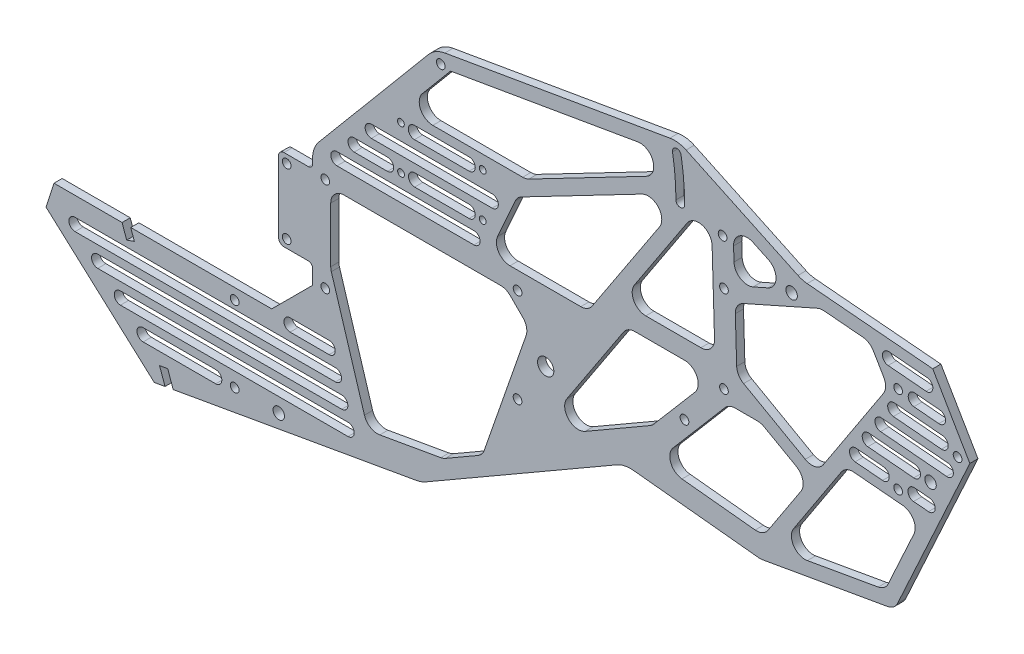
SolidWorks part; units mm, degrees
ref_plane "Front Plane" through (0, 0, 0) normal (0, 0, 1) x (1, 0, 0)
ref_plane "Top Plane" through (0, 0, 0) normal (0, 1, 0) x (1, 0, 0)
ref_plane "Right Plane" through (0, 0, 0) normal (1, 0, 0) x (0, 0, -1)
sketch "Sketch1" plane through (0, 0, 0) normal (0, 0, 1) x (1, 0, 0)
  line L0 (-2, -20.1357) -> (-28.6473, -20.1357) construction
  line L1 (-28.6473, -15.5958) -> (-2, -15.5958) construction
  line L2 (46.6267, -12.6057) -> (-36.9862, -12.6057) construction
  line L3 (-36.9862, -8.0658) -> (46.6267, -8.0658) construction
  line L4 (44.3092, -5.0757) -> (-45.3251, -5.0757) construction
  line L5 (-45.3251, -0.5358) -> (44.3092, -0.5358) construction
  line L6 (41.9917, 2.4543) -> (-53.664, 2.4543) construction
  line L7 (-53.664, 6.9942) -> (41.9917, 6.9942) construction
  line L8 (39.6742, 9.9843) -> (25.3518, 9.9843) construction
  line L9 (25.3518, 14.5242) -> (39.6742, 14.5242) construction
  line L10 (-2, -20.1357) -> (-28.6473, -20.1357)
  line L11 (-28.6473, -15.5958) -> (-2, -15.5958)
  line L12 (46.6267, -12.6057) -> (-36.9862, -12.6057)
  line L13 (-36.9862, -8.0658) -> (46.6267, -8.0658)
  line L14 (44.3092, -5.0757) -> (-45.3251, -5.0757)
  line L15 (-45.3251, -0.5358) -> (44.3092, -0.5358)
  line L16 (41.9917, 2.4543) -> (-53.664, 2.4543)
  line L17 (-53.664, 6.9942) -> (41.9917, 6.9942)
  line L18 (39.6742, 9.9843) -> (25.3518, 9.9843)
  line L19 (25.3518, 14.5242) -> (39.6742, 14.5242)
  line L20 (80.7464, -2.2866) -> (58.3209, -6.2408) construction
  line L21 (106.2441, 62.0298) -> (110.8759, 57.3979) construction
  line L22 (45.2764, 63.4942) -> (102.7085, 63.4942) construction
  line L23 (40.2764, 38.2462) -> (40.2764, 58.4942) construction
  line L24 (52.6739, -2.7875) -> (40.4976, 36.7755) construction
  line L25 (112.0626, 52.2191) -> (96.66, 7.9568) construction
  line L26 (33.6064, 69.3545) -> (33.6064, 67.4942)
  line L27 (76.2479, 123.8124) -> (35.946, 75.7824)
  line L28 (164.9022, 141.4902) -> (82.21, 127.2392)
  line L29 (211.9524, 121.3273) -> (170.8618, 140.6821)
  line L30 (261.4848, 116.375) -> (215.3421, 120.412)
  line L31 (275.1174, 93.0694) -> (261.4848, 116.375)
  line L32 (266.371, 74.0309) -> (275.1174, 93.0694)
  line L33 (151.4467, 29.0597) -> (212.4327, 22.7334)
  line L34 (75.0971, -12.8246) -> (145.4149, 27.7734)
  line L35 (-17.6047, -29.7828) -> (71.8336, -14.0124)
  line L36 (-19.6192, -24.1311) -> (-17.6047, -29.7828)
  line L37 (-22.6157, -24.6595) -> (-19.6192, -24.1311)
  line L38 (-20.6012, -30.3112) -> (-22.6157, -24.6595)
  line L39 (-24.5404, -31.0058) -> (-20.6012, -30.3112)
  line L40 (-64.3382, 4.9315) -> (-24.5404, -31.0058)
  line L41 (-61.3936, 13.9942) -> (-64.3382, 4.9315)
  line L42 (-36.3936, 13.9942) -> (-61.3936, 13.9942)
  line L43 (-34.6915, 9.2192) -> (-36.3936, 13.9942)
  line L44 (-31.8657, 10.2264) -> (-34.6915, 9.2192)
  line L45 (-33.2087, 13.9942) -> (-31.8657, 10.2264)
  line L46 (18.6064, 13.9942) -> (-33.2087, 13.9942)
  line L47 (33.6064, 28.9942) -> (18.6064, 13.9942)
  line L48 (33.6064, 34.4942) -> (33.6064, 28.9942)
  line L49 (23.1064, 35.9942) -> (32.1064, 35.9942)
  line L50 (21.1064, 63.9942) -> (21.1064, 37.9942)
  line L51 (32.1064, 65.9942) -> (23.1064, 65.9942)
  line L52 (33.6064, 69.3545) -> (33.6064, 67.4942)
  line L53 (76.2479, 123.8124) -> (35.946, 75.7824)
  line L54 (164.9022, 141.4902) -> (82.21, 127.2392)
  line L55 (211.9524, 121.3273) -> (170.8618, 140.6821)
  line L56 (261.4848, 116.375) -> (215.3421, 120.412)
  line L57 (275.1174, 93.0694) -> (261.4848, 116.375)
  line L58 (266.371, 74.0309) -> (275.1174, 93.0694)
  line L59 (151.4467, 29.0597) -> (212.4327, 22.7334)
  line L60 (75.0971, -12.8246) -> (145.4149, 27.7734)
  line L61 (-17.6047, -29.7828) -> (71.8336, -14.0124)
  line L62 (-19.6192, -24.1311) -> (-17.6047, -29.7828)
  line L63 (-22.6157, -24.6595) -> (-19.6192, -24.1311)
  line L64 (-20.6012, -30.3112) -> (-22.6157, -24.6595)
  line L65 (-24.5404, -31.0058) -> (-20.6012, -30.3112)
  line L66 (-64.3382, 4.9315) -> (-24.5404, -31.0058)
  line L67 (-61.3936, 13.9942) -> (-64.3382, 4.9315)
  line L68 (-36.3936, 13.9942) -> (-61.3936, 13.9942)
  line L69 (-34.6915, 9.2192) -> (-36.3936, 13.9942)
  line L70 (-31.8657, 10.2264) -> (-34.6915, 9.2192)
  line L71 (-33.2087, 13.9942) -> (-31.8657, 10.2264)
  line L72 (18.6064, 13.9942) -> (-33.2087, 13.9942)
  line L73 (33.6064, 28.9942) -> (18.6064, 13.9942)
  line L74 (33.6064, 34.4942) -> (33.6064, 28.9942)
  line L75 (23.1064, 35.9942) -> (32.1064, 35.9942)
  line L76 (21.1064, 63.9942) -> (21.1064, 37.9942)
  line L77 (32.1064, 65.9942) -> (23.1064, 65.9942)
  line L78 (94.4378, 5.2699) -> (82.3782, -1.6927) construction
  line L79 (112.0626, 52.2191) -> (96.66, 7.9568)
  line L80 (94.4378, 5.2699) -> (82.3782, -1.6927)
  line L81 (80.7464, -2.2866) -> (58.3209, -6.2408)
  line L82 (52.6739, -2.7875) -> (40.4976, 36.7755)
  line L83 (40.2764, 38.2462) -> (40.2764, 58.4942)
  line L84 (45.2764, 63.4942) -> (102.7085, 63.4942)
  line L85 (106.2441, 62.0298) -> (110.8759, 57.3979)
  arc A0 (46.6267, -12.6057) -> (46.6267, -8.0658) centre (46.6267, -10.3357) ccw construction
  arc A1 (44.3092, -5.0757) -> (44.3092, -0.5358) centre (44.3092, -2.8057) ccw construction
  circle A2 centre (5, -17.8657) radius 1.6 construction
  arc A3 (-2, -20.1357) -> (-2, -15.5958) centre (-2, -17.8657) ccw construction
  arc A4 (-28.6473, -15.5958) -> (-28.6473, -20.1357) centre (-28.6473, -17.8657) ccw construction
  arc A5 (-36.9862, -8.0658) -> (-36.9862, -12.6057) centre (-36.9862, -10.3357) ccw construction
  arc A6 (-45.3251, -0.5358) -> (-45.3251, -5.0757) centre (-45.3251, -2.8057) ccw construction
  arc A7 (-53.664, 6.9942) -> (-53.664, 2.4543) centre (-53.664, 4.7243) ccw construction
  arc A8 (41.9917, 2.4543) -> (41.9917, 6.9942) centre (41.9917, 4.7243) ccw construction
  arc A9 (39.6742, 9.9843) -> (39.6742, 14.5242) centre (39.6742, 12.2543) ccw construction
  arc A10 (25.3518, 14.5242) -> (25.3518, 9.9843) centre (25.3518, 12.2543) ccw construction
  circle A11 centre (5, 9.9942) radius 1.6 construction
  arc A12 (46.6267, -12.6057) -> (46.6267, -8.0658) centre (46.6267, -10.3357) ccw
  arc A13 (35.946, 75.7824) -> (33.6064, 69.3545) centre (43.6064, 69.3545) ccw
  arc A14 (82.21, 127.2392) -> (76.2479, 123.8124) centre (83.9084, 117.3845) ccw
  arc A15 (170.8618, 140.6821) -> (164.9022, 141.4902) centre (166.6006, 131.6355) ccw
  arc A16 (211.9524, 121.3273) -> (215.3421, 120.412) centre (216.2136, 130.3739) ccw
  arc A17 (266.371, 74.0309) -> (267.1092, 64.3518) centre (275.4579, 69.8563) ccw
  arc A18 (217.8289, 20.4471) -> (267.1092, 64.3518) centre (239.2664, 45.9942) ccw
  arc A19 (217.8289, 20.4471) -> (212.4327, 22.7334) centre (211.4009, 12.7868) ccw
  arc A20 (151.4467, 29.0597) -> (145.4149, 27.7734) centre (150.4149, 19.1131) ccw
  arc A21 (71.8336, -14.0124) -> (75.0971, -12.8246) centre (70.0971, -4.1643) ccw
  arc A22 (33.6064, 34.4942) -> (32.1064, 35.9942) centre (32.1064, 34.4942) ccw
  arc A23 (21.1064, 37.9942) -> (23.1064, 35.9942) centre (23.1064, 37.9942) ccw
  arc A24 (23.1064, 65.9942) -> (21.1064, 63.9942) centre (23.1064, 63.9942) ccw
  arc A25 (32.1064, 65.9942) -> (33.6064, 67.4942) centre (32.1064, 67.4942) ccw
  arc A26 (35.946, 75.7824) -> (33.6064, 69.3545) centre (43.6064, 69.3545) ccw
  arc A27 (82.21, 127.2392) -> (76.2479, 123.8124) centre (83.9084, 117.3845) ccw
  arc A28 (170.8618, 140.6821) -> (164.9022, 141.4902) centre (166.6006, 131.6355) ccw
  arc A29 (211.9524, 121.3273) -> (215.3421, 120.412) centre (216.2136, 130.3739) ccw
  arc A30 (266.371, 74.0309) -> (267.1092, 64.3518) centre (275.4579, 69.8563) ccw
  arc A31 (217.8289, 20.4471) -> (267.1092, 64.3518) centre (239.2664, 45.9942) ccw
  arc A32 (217.8289, 20.4471) -> (212.4327, 22.7334) centre (211.4009, 12.7868) ccw
  arc A33 (151.4467, 29.0597) -> (145.4149, 27.7734) centre (150.4149, 19.1131) ccw
  arc A34 (71.8336, -14.0124) -> (75.0971, -12.8246) centre (70.0971, -4.1643) ccw
  arc A35 (33.6064, 34.4942) -> (32.1064, 35.9942) centre (32.1064, 34.4942) ccw
  arc A36 (21.1064, 37.9942) -> (23.1064, 35.9942) centre (23.1064, 37.9942) ccw
  arc A37 (23.1064, 65.9942) -> (21.1064, 63.9942) centre (23.1064, 63.9942) ccw
  arc A38 (32.1064, 65.9942) -> (33.6064, 67.4942) centre (32.1064, 67.4942) ccw
  arc A39 (44.3092, -5.0757) -> (44.3092, -0.5358) centre (44.3092, -2.8057) ccw
  circle A40 centre (5, -17.8657) radius 1.6
  arc A41 (-2, -20.1357) -> (-2, -15.5958) centre (-2, -17.8657) ccw
  arc A42 (-28.6473, -15.5958) -> (-28.6473, -20.1357) centre (-28.6473, -17.8657) ccw
  arc A43 (-36.9862, -8.0658) -> (-36.9862, -12.6057) centre (-36.9862, -10.3357) ccw
  arc A44 (-45.3251, -0.5358) -> (-45.3251, -5.0757) centre (-45.3251, -2.8057) ccw
  arc A45 (-53.664, 6.9942) -> (-53.664, 2.4543) centre (-53.664, 4.7243) ccw
  arc A46 (41.9917, 2.4543) -> (41.9917, 6.9942) centre (41.9917, 4.7243) ccw
  arc A47 (39.6742, 9.9843) -> (39.6742, 14.5242) centre (39.6742, 12.2543) ccw
  arc A48 (25.3518, 14.5242) -> (25.3518, 9.9843) centre (25.3518, 12.2543) ccw
  circle A49 centre (5, 9.9942) radius 1.6
  circle A50 centre (24.1064, 38.9942) radius 1.6 construction
  circle A51 centre (38.2764, 30.3942) radius 1.6 construction
  circle A52 centre (24.1064, 38.9942) radius 1.6
  circle A53 centre (38.2764, 30.3942) radius 1.6
  circle A54 centre (24.1064, 62.9942) radius 1.6 construction
  circle A55 centre (38.2764, 64.9942) radius 1.6 construction
  circle A56 centre (24.1064, 62.9942) radius 1.6
  circle A57 centre (38.2764, 64.9942) radius 1.6
  arc A58 (167.1243, 122.9242) -> (170.3243, 122.9242) centre (168.7243, 122.9242) ccw construction
  arc A59 (169.0226, 138.1414) -> (165.8691, 137.5979) centre (167.4459, 137.8696) ccw construction
  arc A60 (170.3243, 122.9242) -> (169.0226, 138.1414) centre (80.7243, 122.9242) ccw construction
  arc A61 (167.1243, 122.9242) -> (165.8691, 137.5979) centre (80.7243, 122.9242) ccw construction
  circle A62 centre (80.7243, 122.9242) radius 1.6 construction
  arc A63 (167.1243, 122.9242) -> (170.3243, 122.9242) centre (168.7243, 122.9242) ccw
  arc A64 (169.0226, 138.1414) -> (165.8691, 137.5979) centre (167.4459, 137.8696) ccw
  arc A65 (170.3243, 122.9242) -> (169.0226, 138.1414) centre (80.7243, 122.9242) ccw
  arc A66 (167.1243, 122.9242) -> (165.8691, 137.5979) centre (80.7243, 122.9242) ccw
  circle A67 centre (80.7243, 122.9242) radius 1.6
  arc A68 (106.2441, 62.0298) -> (102.7085, 63.4942) centre (102.7085, 58.4942) ccw construction
  arc A69 (45.2764, 63.4942) -> (40.2764, 58.4942) centre (45.2764, 58.4942) ccw construction
  arc A70 (40.2764, 38.2462) -> (40.4976, 36.7755) centre (45.2764, 38.2462) ccw construction
  arc A71 (52.6739, -2.7875) -> (58.3209, -6.2408) centre (57.4527, -1.3168) ccw construction
  arc A72 (112.0626, 52.2191) -> (110.8759, 57.3979) centre (107.3404, 53.8624) ccw construction
  arc A73 (94.4378, 5.2699) -> (96.66, 7.9568) centre (91.9378, 9.6) ccw construction
  arc A74 (80.7464, -2.2866) -> (82.3782, -1.6927) centre (79.8782, 2.6375) ccw construction
  arc A75 (112.0626, 52.2191) -> (110.8759, 57.3979) centre (107.3404, 53.8624) ccw
  arc A76 (94.4378, 5.2699) -> (96.66, 7.9568) centre (91.9378, 9.6) ccw
  arc A77 (80.7464, -2.2866) -> (82.3782, -1.6927) centre (79.8782, 2.6375) ccw
  arc A78 (52.6739, -2.7875) -> (58.3209, -6.2408) centre (57.4527, -1.3168) ccw
  arc A79 (40.2764, 38.2462) -> (40.4976, 36.7755) centre (45.2764, 38.2462) ccw
  arc A80 (45.2764, 63.4942) -> (40.2764, 58.4942) centre (45.2764, 58.4942) ccw
  arc A81 (106.2441, 62.0298) -> (102.7085, 63.4942) centre (102.7085, 58.4942) ccw
  circle A82 centre (108.9365, 30.3942) radius 1.6 construction
  circle A83 centre (119.2664, 45.9942) radius 3 construction
  circle A84 centre (108.9365, 64.9942) radius 1.6 construction
  circle A85 centre (108.9365, 30.3942) radius 1.6
  circle A86 centre (119.2664, 45.9942) radius 3
  circle A87 centre (108.9365, 64.9942) radius 1.6
  circle A88 centre (21.1867, -17.8657) radius 2.1 construction
  circle A89 centre (21.1867, -17.8657) radius 2.1
  point P111 (69.5337, -4.2637)
  dimension "D1" = 0
extrude "Boss-Extrude1" add sketch "Sketch1" along normal blind 3
sketch "Sketch2" plane through (0, 0, 3) normal (0, 0, 1) x (1, 0, 0)
  line L0 (151.4467, 29.0597) -> (212.4327, 22.7334) construction
  line L1 (266.371, 74.0309) -> (275.1174, 93.0694) construction
  line L2 (151.4467, 29.0597) -> (241.4229, 19.7261)
  line L3 (241.4229, 19.7261) -> (275.1174, 93.0694)
  line L4 (275.1174, 93.0694) -> (318.5318, -44.2627)
  line L5 (318.5318, -44.2627) -> (151.4467, 29.0597)
extrude "Cut-Extrude1" cut sketch "Sketch2" against normal blind 3
sketch "Sketch3" plane through (0, 0, 3) normal (0, 0, 1) x (1, 0, 0)
  line L0 (198.2297, 24.2068) -> (247.4701, 32.8892)
  line L1 (151.4467, 29.0597) -> (241.4229, 19.7261) construction
  line L2 (241.4229, 19.7261) -> (275.1174, 93.0694) construction
  line L3 (247.4701, 32.8892) -> (241.4229, 19.7261)
  line L4 (241.4229, 19.7261) -> (198.2297, 24.2068)
  line L5 (-17.6047, -29.7828) -> (71.8336, -14.0124) construction
  dimension "D1" = 50
extrude "Cut-Extrude2" cut sketch "Sketch3" against normal blind 3
sketch "Sketch4" plane through (0, 0, 3) normal (0, 0, 1) x (1, 0, 0)
  circle A0 centre (184.7676, 103.569) radius 1.6
  circle A1 centre (184.7676, 71.569) radius 1.6
  circle A2 centre (248.7676, 103.569) radius 1.6
  circle A3 centre (248.7676, 71.569) radius 1.6
  circle A4 centre (66.0577, 96.9942) radius 1.25
  circle A5 centre (96.1205, 96.9942) radius 1.25
  circle A6 centre (66.1205, 80.9942) radius 1.25
  circle A7 centre (96.1205, 80.9942) radius 1.25
  dimension "D1" = 3.2
  dimension "D2" = 2.5
extrude "Cut-Extrude3" cut sketch "Sketch4" against normal blind 3
sketch "Sketch5" plane through (0, 0, 3) normal (0, 0, 1) x (1, 0, 0)
  line L0 (275.1174, 93.0694) -> (261.4848, 116.375) construction
  line L1 (247.4701, 32.8892) -> (275.1174, 93.0694) construction
  line L2 (261.4848, 116.375) -> (215.3421, 120.412) construction
  line L3 (261.4848, 116.375) -> (175.0201, 123.9397) construction
  line L4 (174.2676, 116.569) -> (174.2676, 58.569) construction
  line L5 (174.2676, 58.569) -> (259.2676, 58.569) construction
  circle A0 centre (184.2676, 120.1192) radius 1.6
  circle A1 centre (170.2676, 54.569) radius 1.6
  circle A2 centre (270.6134, 92.8471) radius 1.6
  circle A3 centre (209.6414, 114.6168) radius 2.1 construction
  circle A4 centre (260.6856, 79.8763) radius 2.1 construction
  circle A5 centre (209.6414, 114.6168) radius 2.1
  circle A6 centre (260.6856, 79.8763) radius 2.1
  point P18 (175.0406, 124.1742)
  point P20 (177.4759, 119.7096)
  point P21 (178.4254, 120.6303)
  dimension "D1" = 3.2
  dimension "D2" = 4
  dimension "D3" = 4
  dimension "D4" = 3
  dimension "D5" = 10
  dimension "D6" = 4
  dimension "D7" = 4
extrude "Cut-Extrude4" cut sketch "Sketch5" against normal blind 3
sketch "Sketch6" plane through (0, 0, 3) normal (0, 0, 1) x (1, 0, 0)
  line L0 (132.1655, 71.4942) -> (84.696, 71.4942) construction
  line L1 (161.0949, 111.3374) -> (136.3415, 73.7445) construction
  line L2 (82.3875, 80.9294) -> (154.6103, 118.5223) construction
  line L3 (156.2676, 125.0217) -> (54.5167, 72.0591) construction
  line L4 (48.3779, 79.7082) -> (83.6011, 121.6854) construction
  line L5 (85.3897, 122.7135) -> (153.1099, 134.3842) construction
  line L6 (134.8598, 71.4942) -> (98.4618, 71.4942)
  line L7 (161.0949, 111.3374) -> (134.8598, 71.4942)
  line L8 (108.7652, 94.6593) -> (154.6103, 118.5223)
  line L9 (156.2676, 125.0217) -> (112.0276, 101.9942)
  line L10 (67.0782, 101.9942) -> (84.3071, 122.5269)
  line L11 (84.3071, 122.5269) -> (153.1099, 134.3842)
  line L12 (67.0782, 101.9942) -> (112.0276, 101.9942)
  line L13 (108.7652, 94.6593) -> (98.4618, 71.4942)
  line L14 (42.5653, 73.7642) -> (92.9047, 73.7642) construction
  line L15 (42.5653, 76.0341) -> (92.9047, 76.0341)
  line L16 (42.5653, 71.4942) -> (92.9047, 71.4942)
  line L17 (48.8838, 81.2942) -> (61.1205, 81.2942) construction
  line L18 (48.8838, 83.5641) -> (61.1205, 83.5641)
  line L19 (48.8838, 79.0242) -> (61.1205, 79.0242)
  line L20 (71.1205, 81.2942) -> (91.1205, 81.2942) construction
  line L21 (71.1205, 83.5641) -> (91.1205, 83.5641)
  line L22 (71.1205, 79.0242) -> (91.1205, 79.0242)
  line L23 (55.2022, 88.8242) -> (99.6031, 88.8242) construction
  line L24 (55.2022, 91.0941) -> (99.6031, 91.0941)
  line L25 (55.2022, 86.5542) -> (99.6031, 86.5542)
  line L26 (71.0577, 96.3542) -> (91.1205, 96.3542) construction
  line L27 (71.0577, 98.6241) -> (91.1205, 98.6241)
  line L28 (71.0577, 94.0842) -> (91.1205, 94.0842)
  line L29 (42.5653, 73.7642) -> (55.2022, 88.8242) construction
  line L30 (76.2479, 123.8124) -> (35.946, 75.7824) construction
  line L31 (92.9047, 73.7642) -> (99.6031, 88.8242) construction
  arc A0 (42.5653, 76.0341) -> (42.5653, 71.4942) centre (42.5653, 73.7642) ccw
  arc A1 (92.9047, 71.4942) -> (92.9047, 76.0341) centre (92.9047, 73.7642) ccw
  arc A2 (39.6742, 9.9843) -> (39.6742, 14.5242) centre (39.6742, 12.2543) ccw construction
  arc A3 (48.8838, 83.5641) -> (48.8838, 79.0242) centre (48.8838, 81.2942) ccw
  arc A4 (61.1205, 79.0242) -> (61.1205, 83.5641) centre (61.1205, 81.2942) ccw
  arc A5 (71.1205, 83.5641) -> (71.1205, 79.0242) centre (71.1205, 81.2942) ccw
  arc A6 (91.1205, 79.0242) -> (91.1205, 83.5641) centre (91.1205, 81.2942) ccw
  arc A7 (55.2022, 91.0941) -> (55.2022, 86.5542) centre (55.2022, 88.8242) ccw
  arc A8 (99.6031, 86.5542) -> (99.6031, 91.0941) centre (99.6031, 88.8242) ccw
  arc A9 (71.0577, 98.6241) -> (71.0577, 94.0842) centre (71.0577, 96.3542) ccw
  arc A10 (91.1205, 94.0842) -> (91.1205, 98.6241) centre (91.1205, 96.3542) ccw
  circle A11 centre (66.1205, 80.9942) radius 1.25 construction
  circle A12 centre (96.1205, 80.9942) radius 1.25 construction
  circle A13 centre (96.1205, 96.9942) radius 1.25 construction
  circle A14 centre (66.0577, 96.9942) radius 1.25 construction
  arc A15 (161.0949, 111.3374) -> (154.6103, 118.5223) centre (156.9189, 114.0871) ccw
  arc A16 (156.2676, 125.0217) -> (153.1099, 134.3842) centre (153.9591, 129.4569) ccw
  point P11 (67.735, 73.7642)
  point P32 (55.0021, 81.2942)
  point P37 (81.1205, 81.2942)
  point P44 (77.4026, 88.8242)
  point P53 (81.0891, 96.3542)
  point P72 (96.1205, 80.9942)
  point P73 (0, 0)
  point P75 (109.5689, 95.0777)
  point P76 (112.0276, 101.9942)
  dimension "D9" = 5
  dimension "D10" = 6
  dimension "D11" = 5
  dimension "D1" = 7.53
  dimension "D2" = 7.53
  dimension "D3" = 7.53
  dimension "D4" = 5
  dimension "D5" = 5
  dimension "D6" = 5
  dimension "D7" = 5
  dimension "D8" = 5
extrude "Cut-Extrude5" cut sketch "Sketch6" against normal blind 3
sketch "Sketch7" plane through (0, 0, 3) normal (0, 0, 1) x (1, 0, 0)
  line L0 (159.965, 100.5296) -> (177.5624, 127.2548) construction
  line L1 (146.7725, 80.4942) -> (179.9411, 130.8673)
  line L2 (183.869, 129.0284) -> (201.5125, 120.7179) construction
  line L3 (188.0599, 127.0544) -> (201.0419, 120.9395)
  line L4 (149.3472, 73.4942) -> (181.1523, 73.4942)
  line L5 (181.1523, 73.4942) -> (158.3971, 46.8156)
  line L6 (158.3971, 46.8156) -> (115.4559, 22.0236)
  line L7 (115.4559, 22.0236) -> (149.3472, 73.4942)
  line L8 (134.8598, 71.4942) -> (161.0949, 111.3374) construction
  line L9 (75.0971, -12.8246) -> (145.4149, 27.7734) construction
  line L10 (179.9411, 130.8673) -> (181.4629, 80.4942)
  line L11 (181.4629, 80.4942) -> (146.7725, 80.4942)
  line L12 (186.6132, 67.569) -> (159.881, 36.2278)
  line L13 (159.881, 36.2278) -> (199.2731, 32.1414)
  line L14 (199.2731, 32.1414) -> (215.9786, 57.6554)
  line L15 (215.9786, 57.6554) -> (198.4056, 67.569)
  line L16 (186.6132, 67.569) -> (198.4056, 67.569)
  line L17 (188.8469, 101.004) -> (189.5324, 78.3155)
  line L18 (189.5324, 78.3155) -> (218.7235, 61.8477)
  line L19 (218.7235, 61.8477) -> (245.0335, 102.0304)
  line L20 (245.0335, 102.0304) -> (238.397, 113.3758)
  line L21 (238.397, 113.3758) -> (220.2717, 114.9616)
  line L22 (220.2717, 114.9616) -> (188.8469, 101.004)
  line L23 (200.9409, 111.8467) -> (188.6838, 106.4026)
  line L24 (188.6838, 106.4026) -> (188.0599, 127.0544)
  line L25 (229.5376, 69.2361) -> (204.0505, 30.3103)
  line L26 (204.0505, 30.3103) -> (244.0207, 37.3581)
  line L27 (244.0207, 37.3581) -> (257.5403, 66.7862)
  line L28 (257.5403, 66.7862) -> (229.5376, 69.2361)
  line L29 (247.4701, 32.8892) -> (198.2297, 24.2068) construction
  line L30 (247.4701, 32.8892) -> (275.1174, 93.0694) construction
  line L31 (151.4467, 29.0597) -> (198.2297, 24.2068) construction
  line L32 (98.4618, 71.4942) -> (134.8598, 71.4942) construction
  line L34 (261.4848, 116.375) -> (215.3421, 120.412) construction
  line L35 (275.1174, 93.0694) -> (261.4848, 116.375) construction
  line L36 (245.288, 111.4982) -> (259.2599, 110.2758) construction
  line L37 (245.4858, 113.7595) -> (259.4578, 112.5371)
  line L38 (245.0901, 109.2369) -> (259.0621, 108.0145)
  line L39 (254.7501, 103.1116) -> (263.9199, 102.3093) construction
  line L40 (254.948, 105.3729) -> (264.1177, 104.5706)
  line L41 (254.5523, 100.8503) -> (263.7221, 100.048)
  line L42 (247.2011, 96.2133) -> (264.8954, 94.6652) construction
  line L43 (247.399, 98.4746) -> (265.0933, 96.9265)
  line L44 (247.0033, 93.9519) -> (264.6976, 92.4039)
  line L45 (242.5201, 89.064) -> (266.799, 86.9399) construction
  line L46 (242.718, 91.3253) -> (266.9969, 89.2012)
  line L47 (242.3223, 86.8027) -> (266.6012, 84.6786)
  line L48 (237.8391, 81.9148) -> (254.712, 80.4386) construction
  line L49 (238.0369, 84.1761) -> (254.9098, 82.6999)
  line L50 (237.6413, 79.6535) -> (254.5142, 78.1773)
  line L51 (233.1581, 74.7656) -> (243.2323, 73.8842) construction
  line L52 (233.3559, 77.0269) -> (243.4301, 76.1455)
  line L53 (232.9602, 72.5043) -> (243.0344, 71.6229)
  line L54 (254.6209, 72.8878) -> (260.1223, 72.4065) construction
  line L55 (254.8187, 75.1491) -> (260.3201, 74.6678)
  line L56 (254.423, 70.6265) -> (259.9244, 70.1452)
  circle A0 centre (119.2664, 45.9942) radius 3 construction
  circle A1 centre (184.2676, 120.1192) radius 1.6 construction
  circle A2 centre (184.7676, 103.569) radius 1.6 construction
  circle A3 centre (209.6414, 114.6168) radius 2.1 construction
  circle A4 centre (170.2676, 54.569) radius 1.6 construction
  circle A5 centre (184.7676, 71.569) radius 1.6 construction
  circle A6 centre (248.7676, 103.569) radius 1.6 construction
  circle A7 centre (248.7676, 71.569) radius 1.6 construction
  arc A8 (245.4858, 113.7595) -> (245.0901, 109.2369) centre (245.288, 111.4982) ccw
  arc A9 (259.0621, 108.0145) -> (259.4578, 112.5371) centre (259.2599, 110.2758) ccw
  arc A10 (254.948, 105.3729) -> (254.5523, 100.8503) centre (254.7501, 103.1116) ccw
  arc A11 (263.7221, 100.048) -> (264.1177, 104.5706) centre (263.9199, 102.3093) ccw
  arc A12 (247.399, 98.4746) -> (247.0033, 93.9519) centre (247.2011, 96.2133) ccw
  arc A13 (264.6976, 92.4039) -> (265.0933, 96.9265) centre (264.8954, 94.6652) ccw
  arc A14 (242.718, 91.3253) -> (242.3223, 86.8027) centre (242.5201, 89.064) ccw
  arc A15 (266.6012, 84.6786) -> (266.9969, 89.2012) centre (266.799, 86.9399) ccw
  arc A16 (238.0369, 84.1761) -> (237.6413, 79.6535) centre (237.8391, 81.9148) ccw
  arc A17 (254.5142, 78.1773) -> (254.9098, 82.6999) centre (254.712, 80.4386) ccw
  arc A18 (233.3559, 77.0269) -> (232.9602, 72.5043) centre (233.1581, 74.7656) ccw
  arc A19 (243.0344, 71.6229) -> (243.4301, 76.1455) centre (243.2323, 73.8842) ccw
  arc A20 (254.8187, 75.1491) -> (254.423, 70.6265) centre (254.6209, 72.8878) ccw
  arc A21 (259.9244, 70.1452) -> (260.3201, 74.6678) centre (260.1223, 72.4065) ccw
  arc A22 (46.6267, -12.6057) -> (46.6267, -8.0658) centre (46.6267, -10.3357) ccw construction
  circle A23 centre (270.6134, 92.8471) radius 1.6 construction
  circle A24 centre (260.6856, 79.8763) radius 2.1 construction
  arc A25 (201.0419, 120.9395) -> (200.9409, 111.8467) centre (198.9113, 116.4162) cw
  point P39 (252.2739, 110.887)
  point P45 (259.335, 102.7104)
  point P67 (256.0483, 95.4392)
  point P82 (254.6596, 88.002)
  point P89 (246.2756, 81.1767)
  point P96 (238.1952, 74.3249)
  point P103 (257.3716, 72.6472)
  point P114 (264.9628, 102.2181)
  point P119 (199.2731, 32.1414)
  dimension "D2" = 10
  dimension "D7" = 4
  dimension "D11" = 1
  dimension "D14" = 4
  dimension "D29" = 4
  dimension "D35" = 6
  dimension "D36" = 6
  dimension "D37" = 6
  dimension "D40" = 5
  dimension "D41" = 5
  dimension "D42" = 5
  dimension "D43" = 5
  dimension "D44" = 5
  dimension "D1" = 10
  dimension "D3" = 8
  dimension "D4" = 5
  dimension "D5" = 5
  dimension "D6" = 4
  dimension "D8" = 4
  dimension "D9" = 4
  dimension "D10" = 4
  dimension "D12" = 7
  dimension "D13" = 4
  dimension "D15" = 4
  dimension "D16" = 4
  dimension "D17" = 2
  dimension "D18" = 4
  dimension "D19" = 5
  dimension "D20" = 4
  dimension "D21" = 5
  dimension "D22" = 5
  dimension "D23" = 4
  dimension "D24" = 7.53
  dimension "D25" = 7.53
  dimension "D26" = 7.53
  dimension "D27" = 7.53
  dimension "D28" = 7.53
  dimension "D30" = 5
  dimension "D31" = 5
  dimension "D32" = 6
  dimension "D33" = 5
  dimension "D34" = 5
  dimension "D38" = 5
  dimension "D39" = 6
extrude "Cut-Extrude6" cut sketch "Sketch7" against normal blind 3
fillet "Fillet1" radius 5 29 edges at (204.0505, 30.3103, 1.5) (186.6132, 67.569, 1.5) (198.4056, 67.569, 1.5) (229.5376, 69.2361, 1.5) (199.2731, 32.1414, 1.5) (244.0207, 37.3581, 1.5) (218.7235, 61.8477, 1.5) (257.5403, 66.7862, 1.5) (245.0335, 102.0304, 1.5) (238.397, 113.3758, 1.5) (188.8469, 101.004, 1.5) (220.2717, 114.9616, 1.5) (189.5324, 78.3155, 1.5) (159.881, 36.2278, 1.5) (115.4559, 22.0236, 1.5) (158.3971, 46.8156, 1.5) (181.1523, 73.4942, 1.5) (149.3472, 73.4942, 1.5) (188.6838, 106.4026, 1.5) (188.0599, 127.0544, 1.5) (181.4629, 80.4942, 1.5) (179.9411, 130.8673, 1.5) (146.7725, 80.4942, 1.5) (134.8598, 71.4942, 1.5) (98.4618, 71.4942, 1.5) (108.7652, 94.6593, 1.5) (67.0782, 101.9942, 1.5) (215.9786, 57.6554, 1.5) (112.0276, 101.9942, 1.5)
fillet "Fillet2" radius 5 2 edges at (198.2297, 24.2068, 1.5) (247.4701, 32.8892, 1.5)
